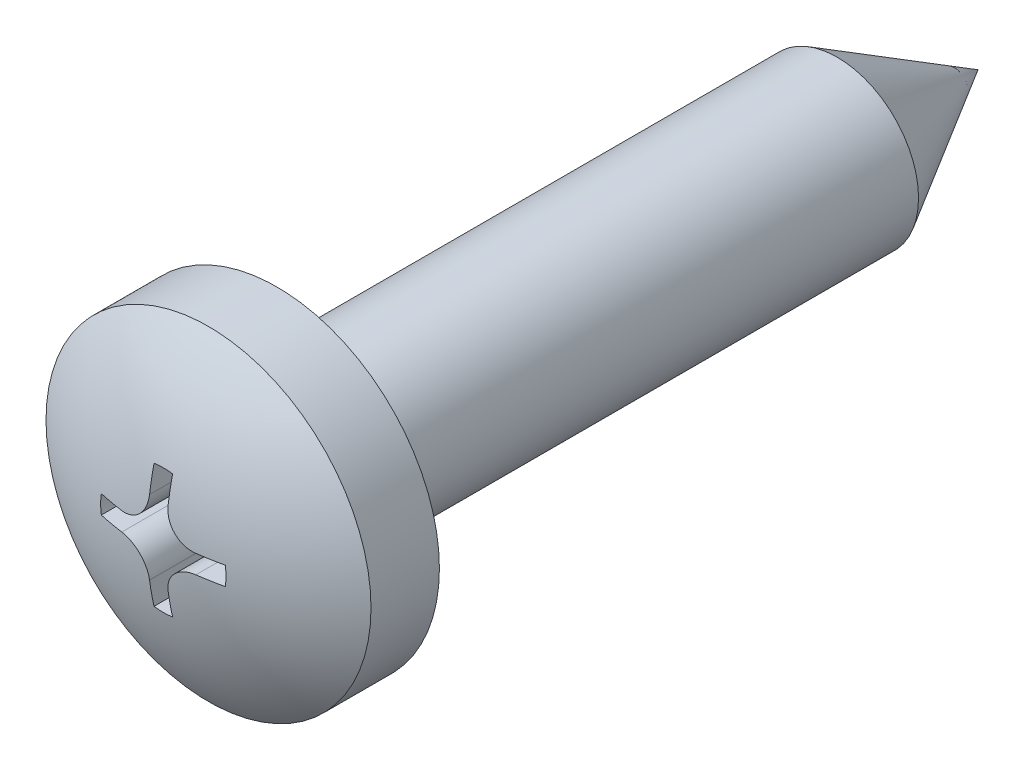
SolidWorks part; units mm, degrees
revolve "基体-旋转" add sketch "草图8" angle 360 about L0
sketch "草图8" plane through (0, 0, 0) normal (1, 0, 0) x (0, 0, -1)
  line L0 (-11.71, 0) -> (1.33, 0) construction
  line L1 (0, 0) -> (-17.7, 0)
  line L4 (-16.5734, 3.5) -> (-15.1, 3.5)
  line L5 (-15.1, 3.5) -> (-15.1, 1.75)
  line L6 (-15.1, 1.75) -> (-3.0311, 1.75)
  line L7 (-3.0311, 1.75) -> (0, 0)
  arc A0 (-17.7, 0) -> (-16.5734, 3.5) centre (-11.7, 0) cw
  dimension "D4" = 6
  dimension "D1" = 15.1
  dimension "D2" = 30
  dimension "D5" = 3.5
  dimension "D3" = 7
  dimension "D6" = 2.6
cosmetic thread "装饰螺纹线1" parameters "D1"=10.6, "D2"=3.031
extrude "切除-拉伸2" cut sketch "草图7" against normal blind 1.55
sketch "草图7" plane through (0, 0, 17.7) normal (0, 0, 1) x (1, 0, 0)
  line L0 (-7.1, 0) -> (5.9, 0) construction
  line L1 (0, 7.5) -> (0, -7) construction
  line L2 (0.2, 1.3351) -> (0.2, 0.7975)
  line L3 (0, 0) -> (4.9858, 4.9858) construction
  line L4 (1.3351, 0.2) -> (0.7975, 0.2)
  line L5 (1.3351, -0.2) -> (0.7975, -0.2)
  line L6 (0.2, -1.3351) -> (0.2, -0.7975)
  line L7 (-0.2, -1.3351) -> (-0.2, -0.7975)
  line L8 (-1.3351, -0.2) -> (-0.7975, -0.2)
  line L9 (-1.3351, 0.2) -> (-0.7975, 0.2)
  line L10 (-0.2, 1.3351) -> (-0.2, 0.7975)
  line L11 (0, 0) -> (-4.9858, 4.9858) construction
  arc A0 (-0.2, 1.3351) -> (0.2, 1.3351) centre (0, 0) cw
  arc A1 (1.3351, -0.2) -> (1.3351, 0.2) centre (0, 0) ccw
  arc A2 (0.7975, 0.2) -> (0.2, 0.7975) centre (0.7975, 0.7975) cw
  arc A3 (-0.7975, 0.2) -> (-0.2, 0.7975) centre (-0.7975, 0.7975) ccw
  arc A4 (-0.2, -1.3351) -> (0.2, -1.3351) centre (0, 0) ccw
  arc A5 (0.7975, -0.2) -> (0.2, -0.7975) centre (0.7975, -0.7975) ccw
  arc A6 (-1.3351, -0.2) -> (-1.3351, 0.2) centre (0, 0) cw
  arc A7 (-0.7975, -0.2) -> (-0.2, -0.7975) centre (-0.7975, -0.7975) cw
  dimension "D10" = 1.35
  dimension "D1" = 0.5975
  dimension "D2" = 0.5975
material "冷镦钢"
ref_plane "前视" through (0, 0, 0) normal (0, 0, 1) x (1, 0, 0)
ref_plane "上视" through (0, 0, 0) normal (0, 1, 0) x (1, 0, 0)
ref_plane "右视" through (0, 0, 0) normal (1, 0, 0) x (0, 0, -1)
sketch "尺寸草图" plane through (0, 0, 0) normal (1, 0, 0) x (0, 0, -1)
  line L0 (-15.1, 7) -> (-15.1, 0)
  line L1 (-15.1, 0) -> (0, 0)
  line L2 (0, 0) -> (0, 3.5)
  point P4 (-12.5, 0)
  point P6 (0, 1.3)
  point P7 (-13.8, 0)
  point P8 (-15.1, 6.9)
  point P9 (-15.1, 1)
  point P10 (-2.7, 0)
  point P11 (-1.55, 0)
  point P12 (-14.58, 0)
  point P13 (-11, 0)
  point P14 (-11.9, 0)
  dimension "l" = 15.1
  dimension "E" = 7
  dimension "K" = 2.6
  dimension "d" = 3.5
  dimension "P" = 1.3
  dimension "A" = 1.3
  dimension "R" = 0.1
  dimension "Rf" = 6
  dimension "HM" = 2.7
  dimension "HH" = 1.55
  dimension "HE" = 0.52
  dimension "Da" = 4.1
  dimension "Yc" = 3.2
ref_plane "基准面6" through (0, 0, 17.7) normal (0, 0, 1) x (1, 0, 0)
sketch "草图9" plane through (0, 0, 0) normal (1, 0, 0) x (0, 0, -1)
  line L0 (-13.8, 1.75) -> (-12.5, 1.75)
  line L1 (-13.8, 1.75) -> (-13.3125, 1.1)
  line L2 (-12.9875, 1.1) -> (-13.3125, 1.1)
  line L3 (-12.9875, 1.1) -> (-12.5, 1.75)
  line L4 (-11.71, 0) -> (1.33, 0) construction
  line L5 (-15.1, -3.5) -> (-15.1, 3.5) construction
  line L6 (-6.912, 0) -> (-2.6011, 0) construction
  line L7 (-16.15, 0) -> (-17.5462, 0) construction
  dimension "D1" = 1.3
  dimension "D2" = 0.325
  dimension "D3" = 0.65
  dimension "D4" = 1.75
  dimension "D5" = 1.3
revolve "切除-旋转1" [suppressed] cut sketch "草图9" angle 360 about L6
pattern_linear "阵列(线性)1" [suppressed] count 8 spacing 1.625
fillet "圆角1" radius 0.1 1 edges at (1.75, 0, 15.1)
equation "\"D16@基准面6\" = \"l@尺寸草图\"+\"K@尺寸草图\""
equation "\"D1@草图8\" = \"l@尺寸草图\""
equation "\"D6@草图8\" = \"K@尺寸草图\""
equation "\"D5@草图8\" = \"d@尺寸草图\""
equation "\"D3@草图8\" = \"E@尺寸草图\""
equation "\"D4@草图8\" = \"Rf@尺寸草图\""
equation "\"D10@草图7\" = \"HM@尺寸草图\"/2"
equation "\"D1@切除-拉伸2\" = \"HH@尺寸草图\""
equation "\"D1@草图9\" = \"P@尺寸草图\""
equation "\"D2@草图9\" = \"D1@草图9\"/4"
equation "\"D3@草图9\" = \"D1@草图9\"/2"
equation "\"D4@草图9\" = \"d@尺寸草图\"/2"
equation "\"D5@草图9\" = \"A@尺寸草图\""
equation "\"D3@阵列(线性)1\" = \"A@尺寸草图\"*5/4"
equation "\"D1@阵列(线性)1\" = (\"l@尺寸草图\"-\"A@尺寸草图\")/\"D3@阵列(线性)1\""
equation "\"D2@装饰螺纹线1\" = \"d@尺寸草图\"*0.866"
equation "\"D1@装饰螺纹线1\" = \"l@尺寸草图\"-\"Yc@尺寸草图\"-\"A@尺寸草图\""
equation "\"D1@圆角1\" = \"R@尺寸草图\""
